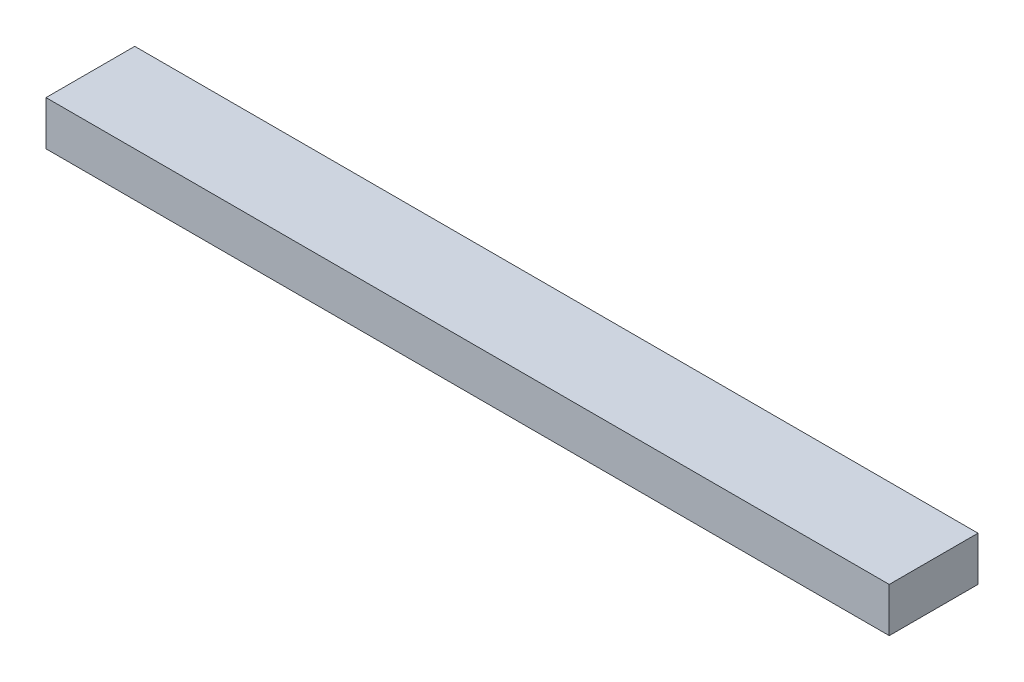
SolidWorks part; units mm, degrees
material "Pine"
ref_plane "Front Plane" through (0, 0, 0) normal (0, 0, 1) x (1, 0, 0)
ref_plane "Top Plane" through (0, 0, 0) normal (0, 1, 0) x (1, 0, 0)
ref_plane "Right Plane" through (0, 0, 0) normal (1, 0, 0) x (0, 0, -1)
sketch "Sketch1" plane through (0, 0, 0) normal (0, 1, 0) x (1, 0, 0)
  line L1 (0, 0) -> (241.3, 0)
  line L2 (0, 0) -> (0, 25.4)
  line L3 (0, 25.4) -> (241.3, 25.4)
  line L4 (241.3, 0) -> (241.3, 25.4)
  dimension "D1" = 241.3
  dimension "D2" = 25.4
extrude "Boss-Extrude1" add sketch "Sketch1" along normal blind 12.7
